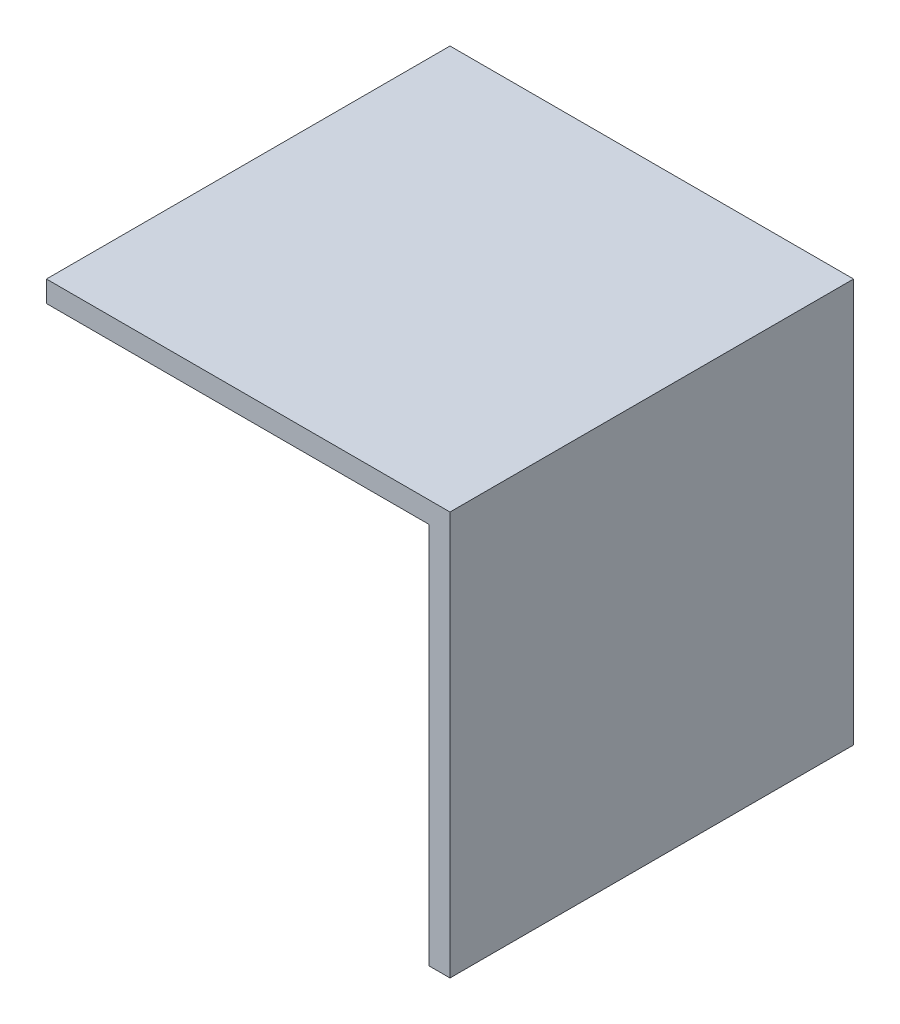
SolidWorks part; units mm, degrees
ref_plane "Front Plane" through (0, 0, 0) normal (0, 0, 1) x (1, 0, 0)
ref_plane "Top Plane" through (0, 0, 0) normal (0, 1, 0) x (1, 0, 0)
ref_plane "Right Plane" through (0, 0, 0) normal (1, 0, 0) x (0, 0, -1)
sketch "Sketch1" plane through (0, 0, 0) normal (0, 0, 1) x (1, 0, 0)
  line L1 (-50, -50) -> (50, -50)
  line L2 (-50, -50) -> (-50, 50)
  line L3 (-50, 50) -> (50, 50)
  line L4 (50, -50) -> (50, 50)
  line L5 (-50, -50) -> (50, 50) construction
  line L6 (-50, 50) -> (50, -50) construction
  point P0 (0, 0)
  dimension "D1" = 100
  dimension "D2" = 100
extrude "Boss-Extrude1" add sketch "Sketch1" along normal blind 5
sketch "Sketch2" plane through (0, 0, 5) normal (0, 0, 1) x (1, 0, 0)
  line L0 (-50, 50) -> (50, 50)
  line L1 (50, 50) -> (50, -50)
  line L2 (-50, 45) -> (45, 45)
  line L3 (45, 45) -> (45, -50)
  line L4 (-50, 50) -> (-50, 45)
  line L5 (45, -50) -> (50, -50)
  dimension "D1" = 5
extrude "Boss-Extrude2" add sketch "Sketch2" along normal blind 95
sketch "Sketch3" plane through (0, 0, 0) normal (0, 0, -1) x (-1, 0, 0)
  line L0 (50, 50) -> (50, -50) construction
  line L1 (50, -50) -> (-50, -50) construction
  circle A0 centre (0, 19.5) radius 13.25
  dimension "D1" = 26.5
  dimension "D2" = 50
  dimension "D3" = 69.5
extrude "Cut-Extrude1" cut sketch "Sketch3" against normal blind 95
sketch "Sketch4" plane through (0, 0, 0) normal (0, 0, -1) x (-1, 0, 0)
  line L0 (-50, -50) -> (50, -50)
  line L1 (50, -50) -> (50, 50)
  line L2 (50, 50) -> (50, -50) construction
  line L3 (-50, -45) -> (45, -45)
  line L4 (45, -45) -> (45, 50)
  line L5 (-50, -45) -> (-50, -50)
  line L6 (45, 50) -> (50, 50)
  dimension "D1" = 5
extrude "Cut-Extrude2" cut sketch "Sketch4" against normal through all
sketch "Sketch5" plane through (50, 0, 0) normal (1, 0, 0) x (0, 0, -1)
  line L0 (-100, -45) -> (-100, 50)
  line L1 (-100, 50) -> (-95, 50)
  line L2 (-100, 50) -> (0, 50) construction
  line L3 (-95, 50) -> (-95, -45)
  line L4 (-100, -45) -> (0, -45) construction
  line L5 (-95, -45) -> (-100, -45)
  dimension "D1" = 5
extrude "Cut-Extrude3" cut sketch "Sketch5" against normal through all
